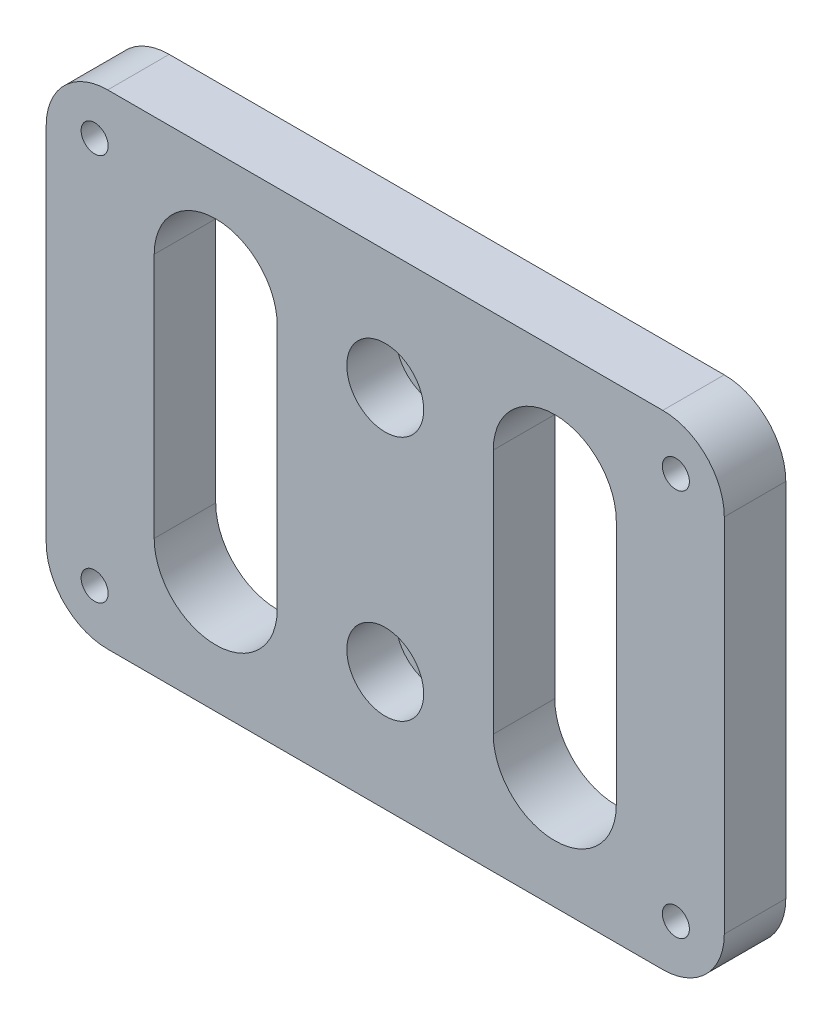
SolidWorks part; units mm, degrees
ref_plane "Front Plane" through (0, 0, 0) normal (0, 0, 1) x (1, 0, 0)
ref_plane "Top Plane" through (0, 0, 0) normal (0, 1, 0) x (1, 0, 0)
ref_plane "Right Plane" through (0, 0, 0) normal (1, 0, 0) x (0, 0, -1)
sketch "Sketch1" plane through (0, 0, 0) normal (0, 0, 1) x (1, 0, 0)
  line L0 (-30, -20) -> (30, -20) construction
  line L1 (-30, -20) -> (-30, 20) construction
  line L2 (30, -20) -> (30, 20) construction
  line L3 (-30, 20) -> (30, 20) construction
  line L4 (-30, -20) -> (30, 20) construction
  line L5 (30, -20) -> (-30, 20) construction
  line L6 (-35, -25) -> (35, -25)
  line L7 (-35, -25) -> (-35, 25)
  line L8 (35, -25) -> (35, 25)
  line L9 (-35, 25) -> (35, 25)
  line L10 (-35, -25) -> (35, 25) construction
  line L11 (35, -25) -> (-35, 25) construction
  line L12 (0, 12.7) -> (0, -12.7) construction
  line L13 (0, 0) -> (-35, 0) construction
  line L14 (0, 0) -> (35, 0) construction
  line L15 (-17.5, -12.7) -> (-17.5, 12.7) construction
  line L16 (-23.85, -12.7) -> (-23.85, 12.7)
  line L17 (-11.15, -12.7) -> (-11.15, 12.7)
  line L18 (17.5, 12.7) -> (17.5, -12.7) construction
  line L19 (23.85, 12.7) -> (23.85, -12.7)
  line L20 (11.15, 12.7) -> (11.15, -12.7)
  circle A0 centre (30, 20) radius 1.397
  circle A1 centre (30, -20) radius 1.397
  circle A2 centre (-30, -20) radius 1.397
  circle A3 centre (-30, 20) radius 1.397
  circle A4 centre (0, 12.7) radius 2.4892
  circle A5 centre (0, -12.7) radius 2.4892
  arc A6 (-23.85, -12.7) -> (-11.15, -12.7) centre (-17.5, -12.7) ccw
  arc A7 (-11.15, 12.7) -> (-23.85, 12.7) centre (-17.5, 12.7) ccw
  arc A8 (23.85, 12.7) -> (11.15, 12.7) centre (17.5, 12.7) ccw
  arc A9 (11.15, -12.7) -> (23.85, -12.7) centre (17.5, -12.7) ccw
  point P1 (0, 0)
  point P2 (0, 0)
  point P24 (-17.5, 0)
  point P30 (17.5, 0)
  dimension "D1" = 2.794
  dimension "D7" = 4.9784
  dimension "D9" = 12.7
  dimension "D2" = 60
  dimension "D3" = 40
  dimension "D4" = 5
  dimension "D5" = 5
  dimension "D6" = 25.4
  dimension "D8" = 25.4
  dimension "D10" = 12.7
extrude "Boss-Extrude1" add sketch "Sketch1" along normal blind 6.35
fillet "Fillet1" radius 6.35 4 edges at (-35, 25, 3.175) (-35, -25, 3.175) (35, -25, 3.175) (35, 25, 3.175)
sketch "Sketch3" plane through (0, 0, 6.35) normal (0, 0, 1) x (1, 0, 0)
  circle A0 centre (0, 12.7) radius 3.9688
  circle A1 centre (0, -12.7) radius 3.9688
  circle A2 centre (0, 12.7) radius 2.4892 construction
  point P7 (0, 0)
  dimension "D1" = 7.9375
extrude "Cut-Extrude1" cut sketch "Sketch3" against normal blind 5.08
